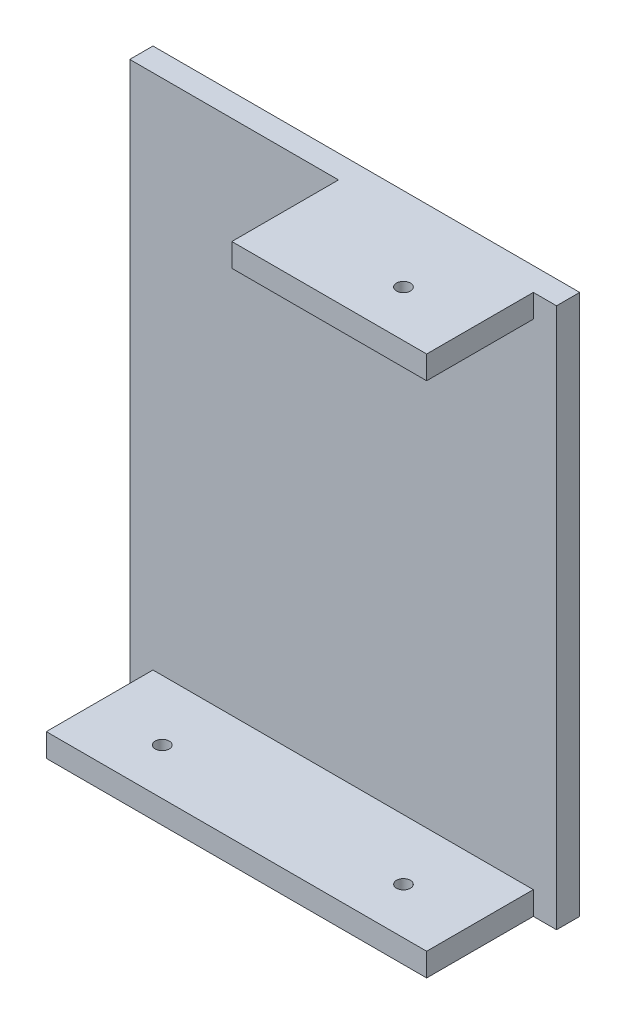
SolidWorks part; units mm, degrees
ref_plane "前基準面" through (0, 0, 0) normal (0, 0, 1) x (1, 0, 0)
ref_plane "上基準面" through (0, 0, 0) normal (0, 1, 0) x (1, 0, 0)
ref_plane "右基準面" through (0, 0, 0) normal (1, 0, 0) x (0, 0, -1)
sketch "草圖1" plane through (0, 0, 0) normal (0, 0, 1) x (1, 0, 0)
  line L1 (-45.1443, 35.3682) -> (46.8557, 35.3682)
  line L2 (-45.1443, 35.3682) -> (-45.1443, -81.1318)
  line L3 (-45.1443, -81.1318) -> (46.8557, -81.1318)
  line L4 (46.8557, 35.3682) -> (46.8557, -81.1318)
  dimension "D1" = 92
  dimension "D2" = 116.5
extrude "填料-伸長1" add sketch "草圖1" along normal blind 5
sketch "草圖2" plane through (0, 0, 5) normal (0, 0, 1) x (1, 0, 0)
  line L0 (-45.1443, -81.1318) -> (46.8557, -81.1318) construction
  line L1 (-40.1443, -81.1318) -> (41.8557, -81.1318)
  line L2 (-40.1443, -81.1318) -> (-40.1443, -76.1318)
  line L3 (-40.1443, -76.1318) -> (41.8557, -76.1318)
  line L4 (41.8557, -81.1318) -> (41.8557, -76.1318)
  line L5 (-45.1443, 35.3682) -> (-45.1443, -81.1318) construction
  line L6 (46.8557, -81.1318) -> (46.8557, 35.3682) construction
  line L7 (46.8557, 35.3682) -> (-45.1443, 35.3682) construction
  line L8 (-0.1443, 35.3682) -> (41.8557, 35.3682)
  line L9 (-0.1443, 35.3682) -> (-0.1443, 30.3682)
  line L10 (-0.1443, 30.3682) -> (41.8557, 30.3682)
  line L11 (41.8557, 35.3682) -> (41.8557, 30.3682)
  dimension "D1" = 5
  dimension "D2" = 5
  dimension "D3" = 5
  dimension "D4" = 5
  dimension "D5" = 106.5
  dimension "D6" = 45
extrude "填料-伸長2" add sketch "草圖2" along normal blind 23
sketch "草圖3" plane through (0, -81.1318, 0) normal (0, -1, 0) x (1, 0, 0)
  line L0 (-40.1443, 28) -> (41.8557, 28) construction
  line L1 (-40.1443, 28) -> (-40.1443, 5) construction
  line L2 (41.8557, 28) -> (41.8557, 5) construction
  circle A0 centre (-25.1443, 18) radius 1.5
  circle A1 centre (26.8557, 18) radius 1.5
  dimension "D1" = 3
  dimension "D2" = 3
  dimension "D3" = 10
  dimension "D4" = 15
  dimension "D5" = 10
  dimension "D6" = 15
extrude "除料-伸長1" cut sketch "草圖3" against normal through all
